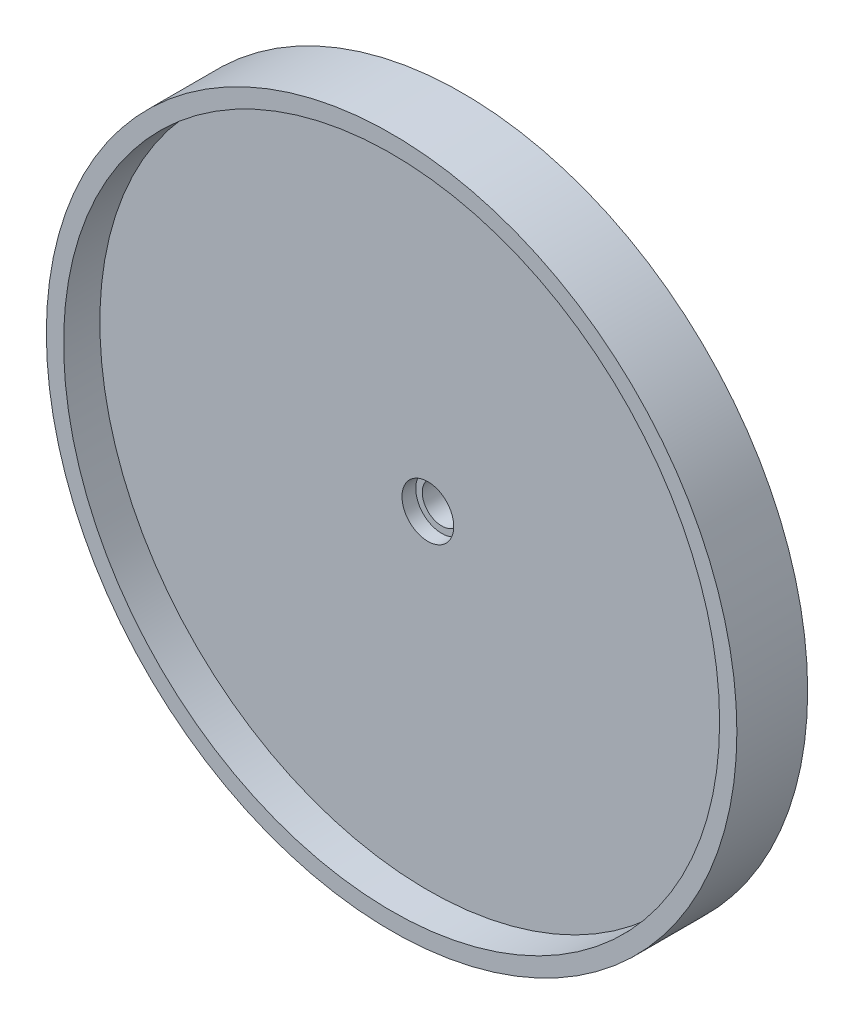
SolidWorks part; units mm, degrees
ref_plane "Front Plane" through (0, 0, 0) normal (0, 0, 1) x (1, 0, 0)
ref_plane "Top Plane" through (0, 0, 0) normal (0, 1, 0) x (1, 0, 0)
ref_plane "Right Plane" through (0, 0, 0) normal (1, 0, 0) x (0, 0, -1)
sketch "Sketch2" plane through (0, 0, 0) normal (1, 0, 0) x (0, 0, -1)
  line L0 (-40.5335, 0) -> (42.2066, 0) construction
  line L1 (0, 63.5) -> (0, 60.325)
  line L2 (0, 60.325) -> (6.6675, 60.325)
  line L3 (6.6675, 60.325) -> (6.6675, 0)
  line L4 (6.6675, 0) -> (13.0175, 0)
  line L5 (13.0175, 0) -> (13.0175, 63.5)
  line L6 (13.0175, 63.5) -> (0, 63.5)
  dimension "D1" = 13.0175
  dimension "D2" = 127
  dimension "D3" = 120.65
  dimension "D4" = 6.35
revolve "Revolve1" add sketch "Sketch2" angle 360 about L0
sketch "Sketch3" plane through (0, 0, -13.0175) normal (0, 0, -1) x (-1, 0, 0)
  circle A0 centre (0, 0) radius 3.5719
  dimension "D1" = 7.1437
extrude "Cut-Extrude1" cut sketch "Sketch3" against normal up to next and the other way through all
sketch "Sketch4" plane through (0, 0, -6.6675) normal (0, 0, 1) x (1, 0, 0)
  circle A0 centre (0, 0) radius 4.7625
  dimension "D1" = 9.525
extrude "Cut-Extrude2" cut sketch "Sketch4" against normal blind 2.54
